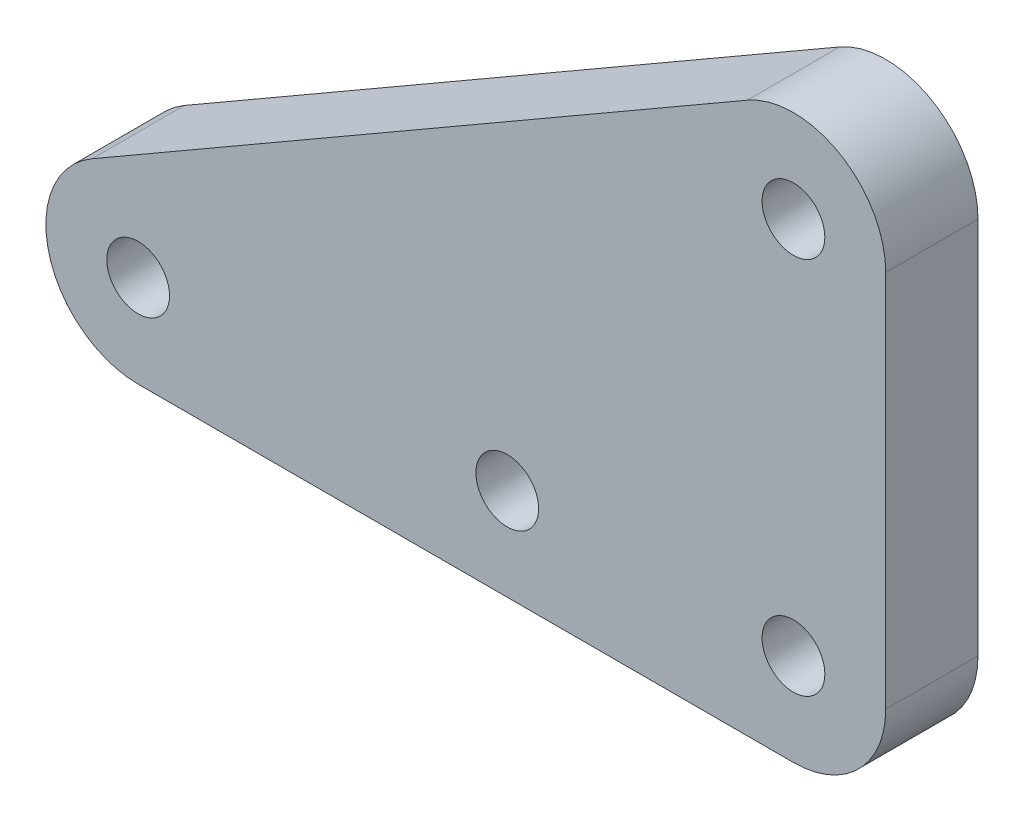
SolidWorks part; units mm, degrees
ref_plane "正面" through (0, 0, 0) normal (0, 0, 1) x (1, 0, 0)
ref_plane "平面" through (0, 0, 0) normal (0, 1, 0) x (1, 0, 0)
ref_plane "右側面" through (0, 0, 0) normal (1, 0, 0) x (0, 0, -1)
sketch "ｽｹｯﾁ1" plane through (0, 0, 0) normal (0, 0, 1) x (1, 0, 0)
  line L0 (0, 0) -> (50.3706, 0)
  line L1 (0, 0) -> (35.507, 20.5)
  line L2 (-18.6603, -5) -> (40.507, 29.1603)
  line L3 (-18.6603, -5) -> (47.1812, -5)
  line L4 (40.507, 29.1603) -> (40.507, -5)
  circle A0 centre (35.507, 20.5) radius 1.7
  circle A1 centre (0, 0) radius 1.7
  circle A2 centre (35.507, 0) radius 1.7
  circle A3 centre (35.507, 20.5) radius 5
  circle A4 centre (35.507, 0) radius 5
  circle A5 centre (0, 0) radius 5
  circle A6 centre (20, 0) radius 1.7
  dimension "D3" = 5
  dimension "D5" = 5
  dimension "D6" = 20
  dimension "D1" = 30
  dimension "D2" = 41
  dimension "D4" = 5
extrude "ﾎﾞｽ - 押し出し1" add sketch "ｽｹｯﾁ1" along normal blind 5
